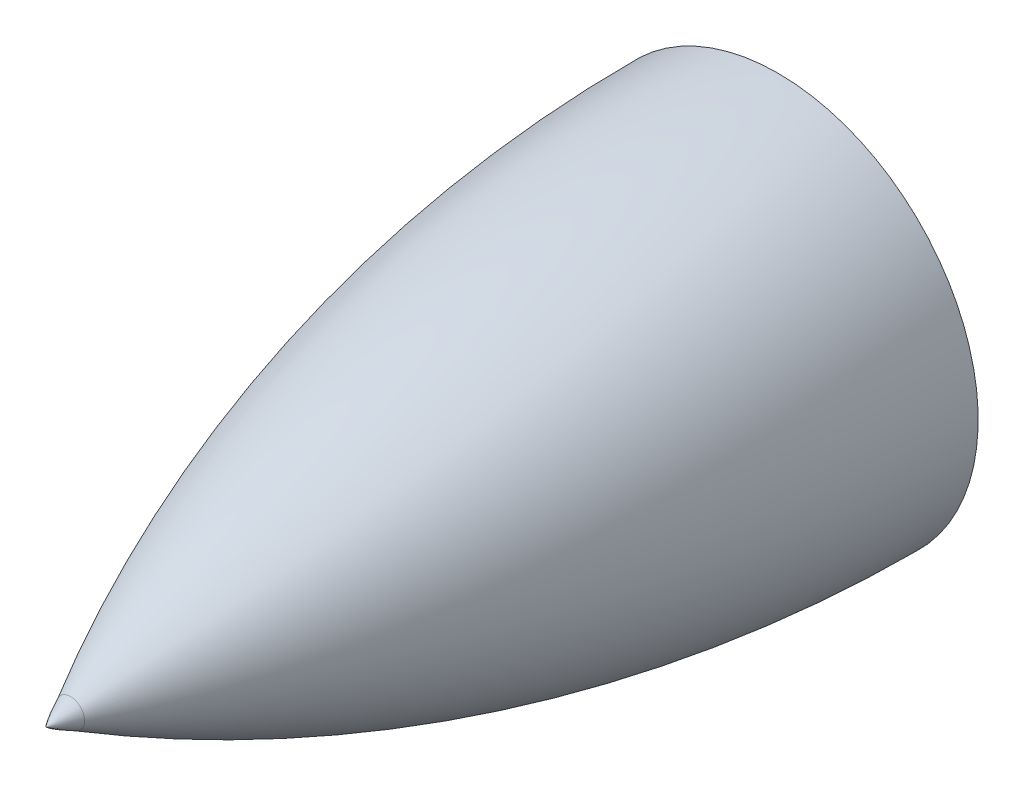
SolidWorks part; units mm, degrees
ref_plane "Front Plane" through (0, 0, 0) normal (0, 0, 1) x (1, 0, 0)
ref_plane "Top Plane" through (0, 0, 0) normal (0, 1, 0) x (1, 0, 0)
ref_plane "Right Plane" through (0, 0, 0) normal (1, 0, 0) x (0, 0, -1)
sketch "Sketch1" plane through (0, 0, 0) normal (1, 0, 0) x (0, 0, -1)
  line L0 (0, 293.3902) -> (0, 294.8902)
  line L1 (0, 253.8902) -> (-150, 253.8902) construction
  line L2 (0, 0) -> (0, 253.8902) construction
  line L5 (0, 253.8902) -> (79, 253.8902) construction
  line L9 (-150, 253.8902) -> (-144.0127, 253.8902)
  line L11 (-34, 289.9033) -> (-34, 291.4135)
  line L12 (79, 288.8902) -> (79, 253.8902) construction
  line L13 (82, 291.8902) -> (82, 253.8902) construction
  line L14 (-3, 288.8902) -> (79, 288.8902) construction
  line L15 (0, 291.8902) -> (82, 291.8902) construction
  line L16 (-3, 288.8902) -> (-3, 291.8748) construction
  line L17 (0, 291.8902) -> (0, 294.8902) construction
  arc A0 (0, 294.8902) -> (-150, 253.8902) centre (0, 0) ccw
  arc A1 (-34, 289.9033) -> (-144.0127, 253.8902) centre (0, 0) ccw
  arc A2 (-3, 291.8748) -> (-148.474, 251.3073) centre (0, 0) ccw construction
  arc A3 (0, 293.3902) -> (-34, 291.4135) centre (0, 0) ccw
  dimension "D1" = 150
  dimension "D2" = 41
  dimension "D4" = 3
revolve "Revolve1" add sketch "Sketch1" angle 360 about L1
sketch "Sketch2" plane through (0, 0, 0) normal (1, 0, 0) x (0, 0, -1)
  line L2 (-150, 253.8902) -> (-145, 253.8902)
  line L3 (-145, 253.8902) -> (-145, 256.7786)
  arc A2 (0, 294.8902) -> (-150, 253.8902) centre (0, 0) ccw construction
  arc A3 (-145, 256.7786) -> (-150, 253.8902) centre (0, 0) ccw
  dimension "D1" = 5
revolve "Cut-Revolve1" cut sketch "Sketch2" angle 360 about L2
sketch "Sketch4" plane through (0, 0, 0) normal (1, 0, 0) x (0, 0, -1)
  line L0 (-145, 253.8902) -> (-150, 253.8902)
  line L1 (-145, 256.7786) -> (-145, 251.0019) construction
  line L3 (-145, 253.8902) -> (-145, 256.7786)
  spline S0 degree 3 poles (-145, 256.7786) (-148.3667, 255.1867) (-150, 254.0655) (-150, 253.8902) knots 0 0 0 0 0.5 0.5 0.5 0.5
  dimension "D1" = 5
revolve "Revolve2" add sketch "Sketch4" angle 360 about L0
